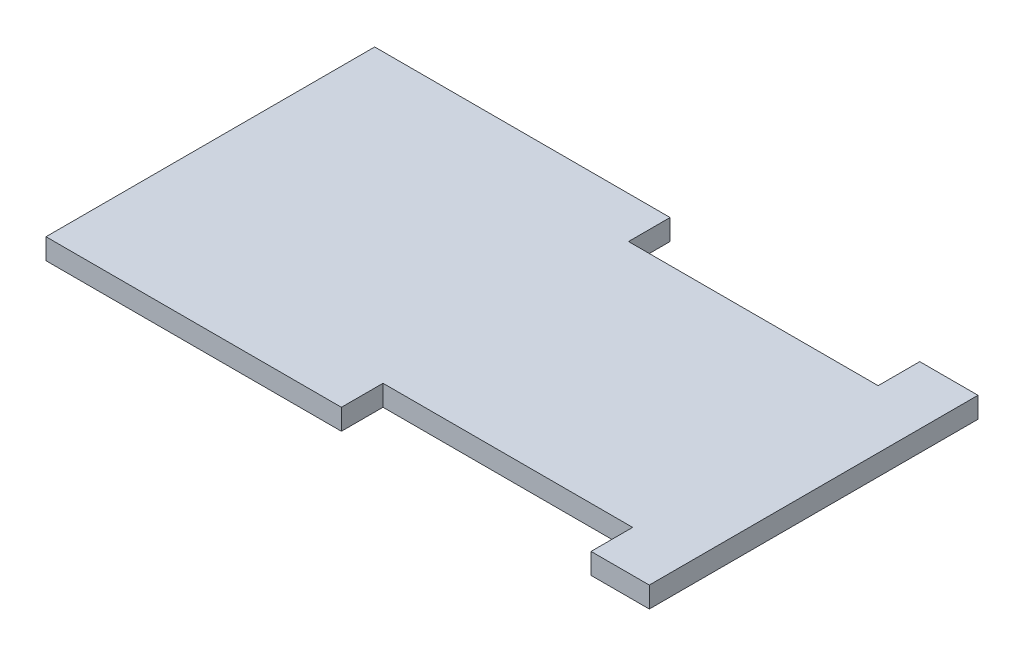
SolidWorks part; units mm, degrees
ref_plane "Plan de face" through (0, 0, 0) normal (0, 0, 1) x (1, 0, 0)
ref_plane "Plan de dessus" through (0, 0, 0) normal (0, 1, 0) x (1, 0, 0)
ref_plane "Plan de droite" through (0, 0, 0) normal (1, 0, 0) x (0, 0, -1)
sketch "Esquisse1" plane through (0, 0, 0) normal (0, 1, 0) x (1, 0, 0)
  line L1 (-48.2678, 34.2577) -> (96.7322, 34.2577)
  line L2 (-48.2678, 34.2577) -> (-48.2678, -44.7423)
  line L3 (-48.2678, -44.7423) -> (96.7322, -44.7423)
  line L4 (96.7322, 34.2577) -> (96.7322, -44.7423)
  dimension "D1" = 145
  dimension "D2" = 79
extrude "Extrusion1" add sketch "Esquisse1" along normal blind 5
sketch "Esquisse2" plane through (0, 5, 0) normal (0, 1, 0) x (1, 0, 0)
  line L0 (96.7322, 34.2577) -> (-48.2678, 34.2577) construction
  line L1 (22.7322, 34.2577) -> (82.7322, 34.2577)
  line L2 (22.7322, 34.2577) -> (22.7322, 24.2577)
  line L3 (22.7322, 24.2577) -> (82.7322, 24.2577)
  line L4 (82.7322, 34.2577) -> (82.7322, 24.2577)
  line L5 (-48.2678, -44.7423) -> (96.7322, -44.7423) construction
  line L6 (22.7322, -44.7423) -> (82.7322, -44.7423)
  line L7 (22.7322, -44.7423) -> (22.7322, -34.7423)
  line L8 (22.7322, -34.7423) -> (82.7322, -34.7423)
  line L9 (82.7322, -44.7423) -> (82.7322, -34.7423)
  line L11 (96.7322, -44.7423) -> (96.7322, 34.2577) construction
  dimension "D1" = 14
  dimension "D2" = 60
  dimension "D3" = 10
  dimension "D4" = 10
extrude "Extrusion2" cut sketch "Esquisse2" against normal up to next
